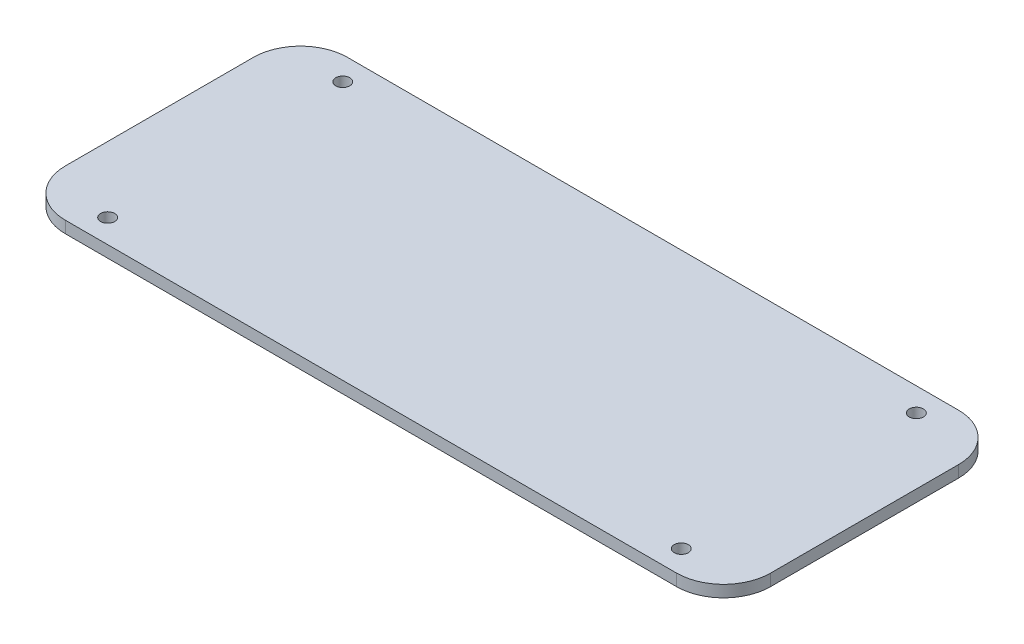
SolidWorks part; units mm, degrees
ref_plane "Front Plane" through (0, 0, 0) normal (0, 0, 1) x (1, 0, 0)
ref_plane "Top Plane" through (0, 0, 0) normal (0, 1, 0) x (1, 0, 0)
ref_plane "Right Plane" through (0, 0, 0) normal (1, 0, 0) x (0, 0, -1)
sketch "Sketch1" plane through (0, 0, 0) normal (0, 1, 0) x (1, 0, 0)
  line L1 (10, 0) -> (140, 0)
  line L2 (0, 10) -> (0, 50)
  line L3 (10, 60) -> (140, 60)
  line L4 (150, 10) -> (150, 50)
  arc A0 (10, 60) -> (0, 50) centre (10, 50) ccw
  arc A1 (0, 10) -> (10, 0) centre (10, 10) ccw
  arc A2 (150, 10) -> (140, 0) centre (140, 10) cw
  arc A3 (140, 60) -> (150, 50) centre (140, 50) cw
  point P7 (0, 60)
  point P10 (0, 0)
  point P13 (150, 0)
  dimension "D3" = 10
  dimension "D4" = 10
  dimension "D5" = 10
  dimension "D6" = 10
  dimension "D1" = 150
  dimension "D2" = 60
extrude "Boss-Extrude1" add sketch "Sketch1" along normal blind 2.5
sketch "Sketch2" plane through (0, 2.5, 0) normal (0, 1, 0) x (1, 0, 0)
  line L0 (0, 50) -> (0, 10) construction
  line L1 (10, 0) -> (140, 0) construction
  line L2 (140, 60) -> (10, 60) construction
  line L3 (75, 55) -> (75, 0) construction
  circle A0 centre (14, 5) radius 1.5
  circle A1 centre (14, 55) radius 1.5
  circle A2 centre (136, 5) radius 1.5
  circle A3 centre (136, 55) radius 1.5
  dimension "D1" = 3
  dimension "D4" = 3
  dimension "D2" = 14
  dimension "D3" = 5
  dimension "D5" = 5
extrude "Cut-Extrude1" cut sketch "Sketch2" against normal through all
